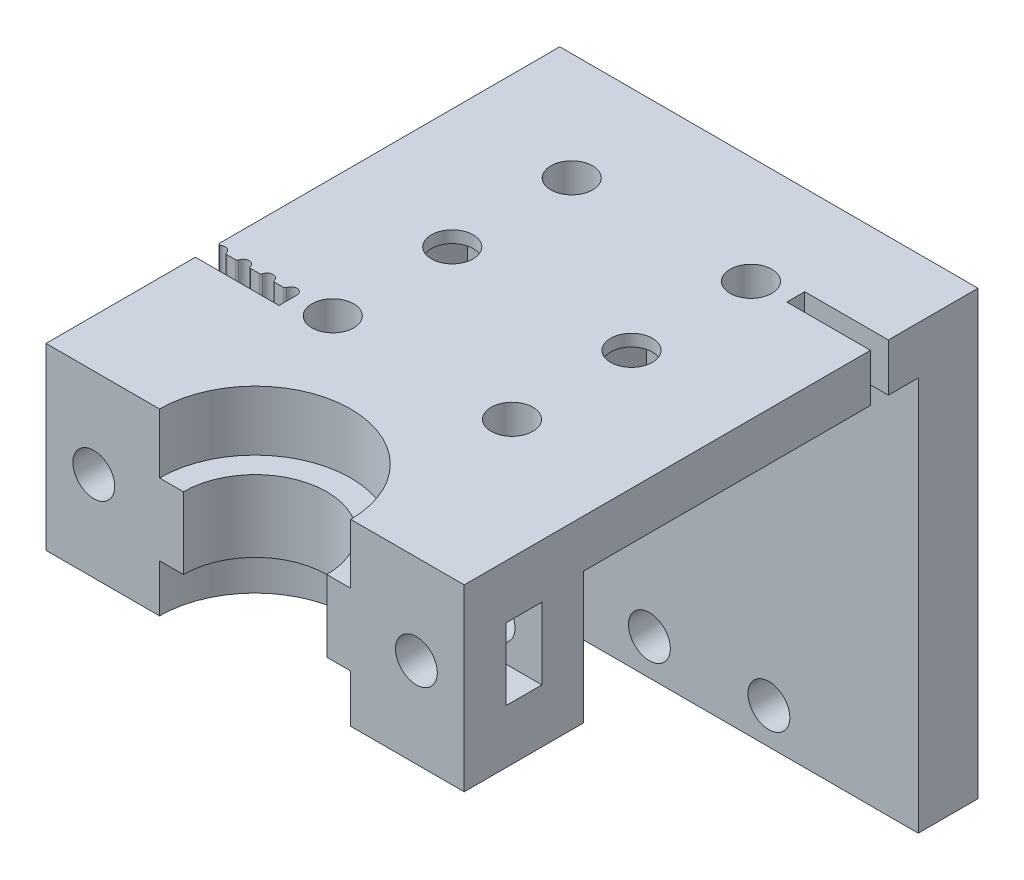
SolidWorks part; units mm, degrees
material "ABS"
ref_plane "Front Plane" through (0, 0, 0) normal (0, 0, 1) x (1, 0, 0)
ref_plane "Top Plane" through (0, 0, 0) normal (0, 1, 0) x (1, 0, 0)
ref_plane "Right Plane" through (0, 0, 0) normal (1, 0, 0) x (0, 0, -1)
sketch "Sketch1" plane through (0, 0, 0) normal (0, 1, 0) x (1, 0, 0)
  line L1 (-17.5, -14) -> (17.5, -14)
  line L2 (-17.5, -14) -> (-17.5, 14)
  line L3 (-17.5, 14) -> (17.5, 14)
  line L4 (17.5, -14) -> (17.5, 14)
  line L5 (-17.5, -14) -> (17.5, 14) construction
  line L6 (-17.5, 14) -> (17.5, -14) construction
  point P0 (0, 0)
  dimension "D1" = 28
  dimension "D2" = 35
extrude "Boss-Extrude1" add sketch "Sketch1" along normal blind 4
sketch "Sketch2" plane through (0, 4, 0) normal (0, 1, 0) x (1, 0, 0)
  line L0 (-17.5, -14) -> (17.5, -14) construction
  line L1 (-17.5, 14) -> (-17.5, -14) construction
  line L2 (-17.5, -14) -> (17.5, -14) construction
  line L3 (17.5, 14) -> (-17.5, 14) construction
  circle A0 centre (-7.5, -10) radius 1.75
  circle A1 centre (-7.5, 10) radius 1.75
  circle A2 centre (7.5, -10) radius 1.75
  circle A3 centre (7.5, 10) radius 1.75
  dimension "D1" = 3.5
  dimension "D2" = 3.5
  dimension "D5" = 3.5
  dimension "D8" = 3.5
  dimension "D3" = 20
  dimension "D4" = 4
  dimension "D6" = 15
  dimension "D7" = 10
  dimension "D9" = 15
  dimension "D10" = 4
  dimension "D11" = 4
extrude "Cut-Extrude1" cut sketch "Sketch2" against normal through all
sketch "Sketch3" plane through (0, 0, 14) normal (0, 0, 1) x (1, 0, 0)
  line L0 (17.5, 4) -> (17.5, 0) construction
  line L1 (-17.5, 4) -> (17.5, 4)
  line L2 (-17.5, 4) -> (-17.5, -11)
  line L3 (-17.5, -11) -> (17.5, -11)
  line L4 (17.5, 4) -> (17.5, -11)
  dimension "D1" = 15
extrude "Boss-Extrude2" add sketch "Sketch3" along normal blind 10
sketch "Sketch5" plane through (0, 0, 24) normal (0, 0, 1) x (1, 0, 0)
  line L0 (0, 4) -> (0, -11) construction
  line L3 (17.5, 4) -> (-17.5, 4) construction
  line L4 (-17.5, -11) -> (17.5, -11) construction
  line L5 (0, 4) -> (8, 4)
  line L6 (8, 4) -> (8, -1)
  line L7 (8, -1) -> (6, -1)
  line L8 (6, -1) -> (6, -7)
  line L9 (6, -7) -> (8, -7)
  line L10 (8, -7) -> (8, -11)
  line L11 (8, -11) -> (0, -11)
  line L12 (0, 4) -> (0, -11)
  dimension "D1" = 8
  dimension "D2" = 5
  dimension "D3" = 2
  dimension "D4" = 6
revolve "Cut-Revolve1" cut sketch "Sketch5" angle 180 about L0
sketch "Sketch6" plane through (0, 0, 24) normal (0, 0, 1) x (1, 0, 0)
  line L0 (-8, -1) -> (-8, 4) construction
  line L1 (-17.5, -11) -> (-8, -11) construction
  line L2 (8, -1) -> (8, 4) construction
  circle A0 centre (-13.5, -3.5) radius 1.75
  circle A2 centre (13.5, -3.5) radius 1.75
  dimension "D1" = 3.5
  dimension "D4" = 3.5
  dimension "D2" = 5.5
  dimension "D3" = 7.5
  dimension "D5" = 5.5
extrude "Cut-Extrude3" cut sketch "Sketch6" against normal blind 10
sketch "Sketch8" plane through (-17.5, 0, 0) normal (-1, 0, 0) x (0, 0, 1)
  line L1 (17.5, -0.5) -> (20.5, -0.5)
  line L2 (17.5, -0.5) -> (17.5, -6.5)
  line L3 (17.5, -6.5) -> (20.5, -6.5)
  line L4 (20.5, -0.5) -> (20.5, -6.5)
  line L5 (24, -11) -> (14, -11) construction
  line L6 (14, 0) -> (14, -11) construction
  dimension "D1" = 6
  dimension "D2" = 4.5
  dimension "D3" = 3
  dimension "D4" = 3.5
extrude "Cut-Extrude4" cut sketch "Sketch8" against normal blind 7
sketch "Sketch9" plane through (17.5, 0, 0) normal (1, 0, 0) x (0, 0, -1)
  line L0 (-14, -11) -> (-14, 0) construction
  line L1 (-20.5, -0.5) -> (-17.5, -0.5)
  line L2 (-20.5, -0.5) -> (-20.5, -6.5)
  line L3 (-20.5, -6.5) -> (-17.5, -6.5)
  line L4 (-17.5, -0.5) -> (-17.5, -6.5)
  line L5 (-24, -11) -> (-14, -11) construction
  dimension "D1" = 6
  dimension "D2" = 3
  dimension "D3" = 3.5
  dimension "D4" = 4.5
extrude "Cut-Extrude5" cut sketch "Sketch9" against normal blind 7
sketch "Sketch7" plane through (0, 0, -14) normal (0, 0, -1) x (-1, 0, 0)
  line L1 (-17.5, 4) -> (17.5, 4)
  line L2 (-17.5, 4) -> (-17.5, -33)
  line L3 (-17.5, -33) -> (17.5, -33)
  line L4 (17.5, 4) -> (17.5, -33)
  line L6 (17.5, 4) -> (17.5, 0) construction
  dimension "D1" = 37
extrude "Boss-Extrude3" add sketch "Sketch7" along normal blind 5
sketch "Sketch10" plane through (0, 0, -19) normal (0, 0, -1) x (-1, 0, 0)
  line L1 (0, 4) -> (0, -33) construction
  line L3 (17.5, 4) -> (-17.5, 4) construction
  line L4 (-17.5, -33) -> (17.5, -33) construction
  circle A1 centre (-5, -30) radius 1.75
  circle A2 centre (5, -30) radius 1.75
  dimension "D1" = 3
  dimension "D2" = 3.5
  dimension "D4" = 3.5
  dimension "D3" = 5
  dimension "D5" = 5
extrude "Cut-Extrude6" cut sketch "Sketch10" against normal blind 5
sketch "Sketch18" plane through (0, 4, 0) normal (0, 1, 0) x (1, 0, 0)
  line L0 (-17.5, -10) -> (-10.5, -10)
  line L1 (-17.5, 19) -> (-17.5, -24) construction
  line L2 (-10.5, -10) -> (-10.5, -11.5)
  line L3 (-10.5, -11.5) -> (-17.5, -11.5)
  line L4 (-17.5, -11.5) -> (-17.5, -10)
  line L5 (17.5, 10) -> (10.5, 10)
  line L6 (17.5, -24) -> (17.5, 19) construction
  line L7 (10.5, 10) -> (10.5, 11.5)
  line L8 (10.5, 11.5) -> (17.5, 11.5)
  line L9 (17.5, 11.5) -> (17.5, 10)
  circle A0 centre (-7.5, -10) radius 1.75 construction
  circle A1 centre (7.5, 10) radius 1.75 construction
  dimension "D4" = 3
  dimension "D1" = 0
  dimension "D2" = 3
  dimension "D3" = 1.5
  dimension "D5" = 0
  dimension "D6" = 1.5
extrude "Cut-Extrude14" cut sketch "Sketch18" against normal through all
sketch "Sketch19" plane through (0, 4, 0) normal (0, 1, 0) x (1, 0, 0)
  line L0 (-17.5, 19) -> (-17.5, -10) construction
  line L1 (17.5, -24) -> (17.5, 10) construction
  circle A0 centre (-7.5, 0) radius 1.75
  circle A1 centre (7.5, 0) radius 1.75
  dimension "D3" = 3.5
  dimension "D4" = 3.5
  dimension "D1" = 10
  dimension "D2" = 10
extrude "Cut-Extrude15" cut sketch "Sketch19" against normal through all
sketch "Sketch20" plane through (0, 0, 0) normal (0, -1, 0) x (1, 0, 0)
  line L1 (10.9641, 0) -> (9.2321, 3)
  line L2 (9.2321, 3) -> (5.7679, 3)
  line L3 (5.7679, 3) -> (4.0359, 0)
  line L4 (4.0359, 0) -> (5.7679, -3)
  line L5 (5.7679, -3) -> (9.2321, -3)
  line L6 (9.2321, -3) -> (10.9641, 0)
  line L7 (-10.9641, 0) -> (-9.2321, -3)
  line L8 (-9.2321, -3) -> (-5.7679, -3)
  line L9 (-5.7679, -3) -> (-4.0359, 0)
  line L10 (-4.0359, 0) -> (-5.7679, 3)
  line L11 (-5.7679, 3) -> (-9.2321, 3)
  line L12 (-9.2321, 3) -> (-10.9641, 0)
  circle A0 centre (7.5, 0) radius 3 construction
  circle A1 centre (-7.5, 0) radius 3 construction
  dimension "D1" = 6
  dimension "D2" = 6
extrude "Cut-Extrude16" cut sketch "Sketch20" against normal blind 3
sketch "Sketch21" plane through (0, 4, 0) normal (0, 1, 0) x (1, 0, 0)
  line L0 (-10.5, -10) -> (-17.5, -10) construction
  circle A0 centre (-17, -10) radius 0.5
  dimension "D1" = 1
extrude "Cut-Extrude17" cut sketch "Sketch21" against normal blind 4
pattern_linear "LPattern2" count 4 spacing 2 along (1, 0, 0) of "Cut-Extrude17"
fillet "Fillet2" radius 0.15 7 edges at (-17.5, 2, 10) (-16.5, 2, 10) (-12.5, 2, 10) (-13.5, 2, 10) (-14.5, 2, 10) (-15.5, 2, 10) (-11.5, 2, 10)
